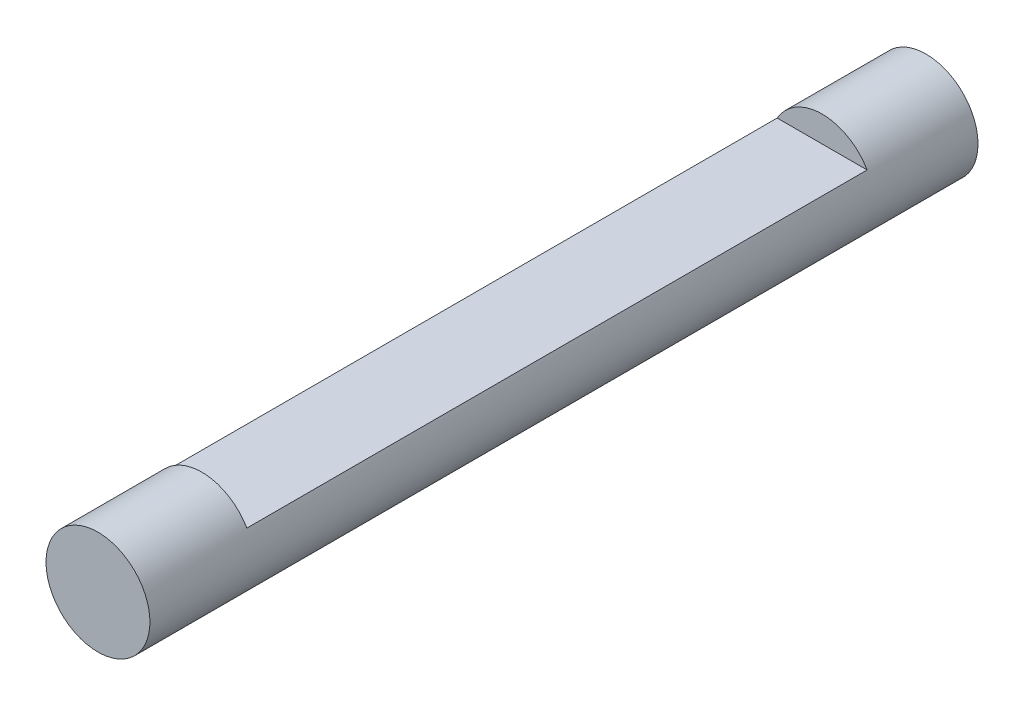
SolidWorks part; units mm, degrees
ref_plane "Front Plane" through (0, 0, 0) normal (0, 0, 1) x (1, 0, 0)
ref_plane "Top Plane" through (0, 0, 0) normal (0, 1, 0) x (1, 0, 0)
ref_plane "Right Plane" through (0, 0, 0) normal (1, 0, 0) x (0, 0, -1)
sketch "Sketch1" plane through (0, 0, 0) normal (0, 0, 1) x (1, 0, 0)
  circle A1 centre (0, 0) radius 4
  dimension "D3" = 8
extrude "Boss-Extrude1" add sketch "Sketch1" along normal up to surface (63.76 mm away)
ref_plane "Plane1" through (0, 4, 0) normal (0, 1, 0) x (1, 0, 0)
ref_plane "Plane2" through (0, 2, 0) normal (0, 1, 0) x (1, 0, 0)
sketch "Sketch2" plane through (0, 2, 0) normal (0, 1, 0) x (1, 0, 0)
  line L0 (0, 0) -> (0, -109.5649) construction
  line L1 (-4, -8) -> (4, -8)
  line L2 (-4, -8) -> (-4, -55.76)
  line L3 (-4, -55.76) -> (4, -55.76)
  line L4 (4, -8) -> (4, -55.76)
  line L5 (4, 0) -> (-4, 0) construction
  line L6 (-4, -63.76) -> (4, -63.76) construction
  point P7 (0, -8)
  dimension "D1" = 8
  dimension "D2" = 8
extrude "Cut-Extrude1" cut sketch "Sketch2" along normal through all
